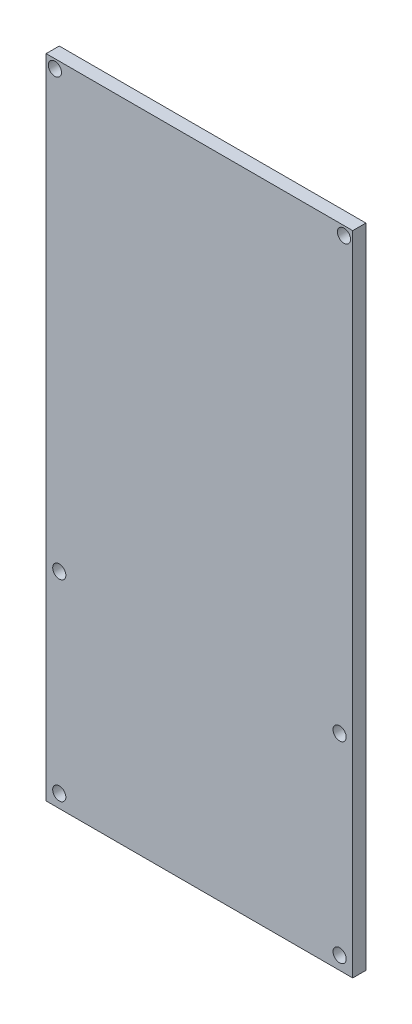
SolidWorks part; units mm, degrees
ref_plane "Alzado" through (0, 0, 0) normal (0, 0, 1) x (1, 0, 0)
ref_plane "Planta" through (0, 0, 0) normal (0, 1, 0) x (1, 0, 0)
ref_plane "Vista lateral" through (0, 0, 0) normal (1, 0, 0) x (0, 0, -1)
sketch "Croquis1" plane through (0, 0, 0) normal (0, 0, 1) x (1, 0, 0)
  line L1 (35, -50) -> (-35, -50)
  line L2 (35, -50) -> (35, 50)
  line L3 (35, 50) -> (-35, 50)
  line L4 (-35, -50) -> (-35, 50)
  line L5 (35, -50) -> (-35, 50) construction
  line L6 (35, 50) -> (-35, -50) construction
  circle A0 centre (-21.5, 36.0433) radius 1
  circle A1 centre (11.5, 36.0433) radius 1
  circle A2 centre (-21.5, 3.02) radius 1
  circle A3 centre (11.5, 3.02) radius 1
  circle A4 centre (-5, 19.52) radius 19
  point P0 (0, 0)
  dimension "D3" = 2
  dimension "D4" = 2
  dimension "D5" = 2
  dimension "D6" = 2
  dimension "D14" = 38
  dimension "D1" = 100
  dimension "D2" = 70
  dimension "D7" = 13.9567
  dimension "D8" = 13.5
  dimension "D9" = 23.5
  dimension "D10" = 46.98
  dimension "D11" = 13.5
  dimension "D12" = 23.5
  dimension "D13" = 46.98
  dimension "D15" = 30
  dimension "D16" = 30.48
extrude "Saliente-Extruir1" add sketch "Croquis1" along normal blind 50
sketch "Croquis3" plane through (0, 0, 0) normal (0, 0, -1) x (-1, 0, 0)
  line L0 (-35, -50) -> (-35, 50) construction
  line L1 (31, -46) -> (-31, -46)
  line L2 (31, -46) -> (31, 46)
  line L3 (31, 46) -> (-31, 46)
  line L4 (-31, -46) -> (-31, 46)
  line L5 (31, -46) -> (-31, 46) construction
  line L6 (31, 46) -> (-31, -46) construction
  line L7 (-35, 50) -> (35, 50) construction
  point P0 (0, 0)
  dimension "D1" = 4
  dimension "D2" = 4
extrude "Cortar-Extruir2" cut sketch "Croquis3" against normal blind 46
sketch "Croquis4" plane through (0, -50, 0) normal (0, -1, 0) x (1, 0, 0)
  line L5 (35, 0) -> (-35, 0)
  line L6 (35, 0) -> (35, 50)
  line L7 (35, 50) -> (-25, 50)
  line L8 (-35, 0) -> (-35, 40)
  line L9 (35, 0) -> (-35, 50) construction
  line L10 (35, 50) -> (-35, 0) construction
  arc A2 (-35, 40) -> (-25, 50) centre (-25, 40) cw
  spline S0 degree 3 poles (24.058, 50) (30.5326, 48.7848) (35.01, 42.4789) (35, 36.1993) knots 0 0 0 0 1 1 1 1
  point P0 (0, 25)
  point P1 (0, 25)
  line M8 (35, 0) -> (35, 50)
  line M9 (35, 50) -> (-35, 50)
  line M10 (-35, 50) -> (-35, 0)
  dimension "D1" = 10
extrude "Cortar-Extruir4" cut sketch "Croquis4" against normal blind 224 contours S0 M9 M8 | A2 M10 M9
sketch "Croquis6" plane through (0, 0, 50) normal (0, 0, 1) x (1, 0, 0)
  line L0 (24.058, 50) -> (24.058, -50) construction
  line L5 (4.558, -22.3804) -> (-6.442, -22.3804)
  line L6 (4.558, -22.3804) -> (4.558, -13.3804)
  line L11 (4.558, -13.3804) -> (-6.442, -13.3804)
  line L12 (-6.442, -22.3804) -> (-6.442, -13.3804)
  line L13 (4.558, -22.3804) -> (-6.442, -13.3804) construction
  line L14 (4.558, -13.3804) -> (-6.442, -22.3804) construction
  circle A0 centre (-7.042, -11.8804) radius 0.8
  circle A1 centre (5.158, -11.8804) radius 0.8
  circle A2 centre (5.158, -24.0804) radius 0.8
  circle A3 centre (-7.042, -24.0804) radius 0.8
  point P0 (1.7793, -18.5636)
  point P5 (-0.942, -17.8804)
  point P6 (-0.942, -17.8804)
  dimension "D5" = 1.6
  dimension "D10" = 1.6
  dimension "D13" = 1.6
  dimension "D16" = 1.6
  dimension "D3" = 9
  dimension "D4" = 11
  dimension "D19" = 25
extrude "Cortar-Extruir5" cut sketch "Croquis6" against normal blind 224
sketch "Croquis7" plane through (-35, 0, 0) normal (-1, 0, 0) x (0, 0, 1)
  line L1 (50, -50) -> (0, -50)
  line L2 (50, -50) -> (50, -57.7685)
  line L3 (10, -97.7685) -> (0, -97.7685)
  line L4 (0, -50) -> (0, -97.7685)
  arc A0 (10, -97.7685) -> (50, -57.7685) centre (10, -57.7685) ccw
  dimension "D1" = 40
extrude "Saliente-Extruir2" add sketch "Croquis7" against normal blind 70
shell "Vaciado4" thickness 10
sketch "Croquis8" plane through (0, 0, 0) normal (0, 0, -1) x (-1, 0, 0)
  line L0 (-31, -46) -> (31, -46) construction
  line L1 (-27.2261, -46) -> (27.4876, -46)
  line L2 (-27.2261, -46) -> (-27.2261, -91.3018)
  line L3 (-27.2261, -91.3018) -> (27.4876, -91.3018)
  line L4 (27.4876, -46) -> (27.4876, -91.3018)
extrude "Cortar-Extruir6" cut sketch "Croquis8" against normal blind 29
sketch "Croquis9" plane through (0, -46, 0) normal (0, 1, 0) x (1, 0, 0)
  line L1 (-27.4876, -29) -> (27.2538, -29)
  line L2 (-27.4876, -29) -> (-27.4876, -43.7498)
  line L3 (-27.4876, -43.7498) -> (27.2538, -43.7498)
  line L4 (27.2538, -29) -> (27.2538, -43.7498)
extrude "Cortar-Extruir7" cut sketch "Croquis9" against normal blind 29
sketch "Croquis10" plane through (0, 0, 0) normal (0, 0, -1) x (-1, 0, 0)
  line L0 (35, 50) -> (35, -97.7685) construction
  line L1 (-35, -97.7685) -> (35, -97.7685) construction
  line L2 (-35, 50) -> (35, 50) construction
  line L3 (-35, -97.7685) -> (-35, 50) construction
  circle A0 centre (-33, 48) radius 1.5
  circle A1 centre (33, 48) radius 1.5
  circle A2 centre (32, -50.898) radius 1.5
  circle A3 centre (-32, -50.898) radius 1.5
  circle A4 centre (-32, -94.7685) radius 1.5
  circle A5 centre (32, -94.7685) radius 1.5
  dimension "D1" = 3
  dimension "D4" = 3
  dimension "D6" = 3
  dimension "D8" = 3
  dimension "D10" = 3
  dimension "D13" = 3
  dimension "D2" = 2
  dimension "D3" = 2
  dimension "D5" = 2
  dimension "D7" = 3
  dimension "D9" = 3
  dimension "D11" = 3
  dimension "D12" = 3
extrude "Cortar-Extruir8" cut sketch "Croquis10" against normal blind 12.7
sketch "Croquis11" plane through (0, 0, 0) normal (0, 0, -1) x (-1, 0, 0)
  line L1 (-35, 50) -> (35, 50)
  line L2 (-35, 50) -> (-35, -97.7685)
  line L3 (-35, -97.7685) -> (35, -97.7685)
  line L4 (35, 50) -> (35, -97.7685)
  circle A0 centre (-33, 48) radius 1.5
  circle A1 centre (33, 48) radius 1.5
  circle A2 centre (32, -50.898) radius 1.5
  circle A3 centre (32, -94.7685) radius 1.5
  circle A4 centre (-32, -94.7685) radius 1.5
  circle A5 centre (-32, -50.898) radius 1.5
extrude "Saliente-Extruir3" add sketch "Croquis11" along normal blind 3
sketch "Croquis12" plane through (0, 0, 50) normal (0, 0, 1) x (1, 0, 0)
  line L1 (-35, 50) -> (35, 50)
  line L2 (-35, 50) -> (-35, -97.7685)
  line L3 (-35, -97.7685) -> (35, -97.7685)
  line L4 (35, 50) -> (35, -97.7685)
extrude "Cortar-Extruir9" cut sketch "Croquis12" against normal blind 50
